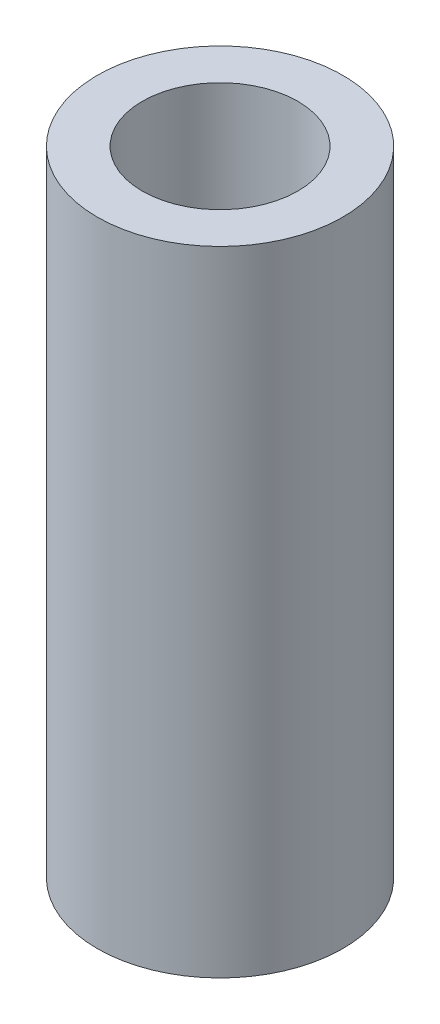
SolidWorks part; units mm, degrees
material "Galvanized Steel"
ref_plane "Front Plane" through (0, 0, 0) normal (0, 0, 1) x (1, 0, 0)
ref_plane "Top Plane" through (0, 0, 0) normal (0, 1, 0) x (1, 0, 0)
ref_plane "Right Plane" through (0, 0, 0) normal (1, 0, 0) x (0, 0, -1)
sketch "Sketch1" plane through (0, 0, 0) normal (0, 1, 0) x (1, 0, 0)
  circle A0 centre (0, 0) radius 12.415
extrude "Boss-Extrude1" add sketch "Sketch1" along normal blind 64.05
sketch "Sketch2" plane through (0, 64.05, 0) normal (0, 1, 0) x (1, 0, 0)
  circle A0 centre (0, 0) radius 7.865
extrude "Cut-Extrude1" cut sketch "Sketch2" against normal blind 64.05
